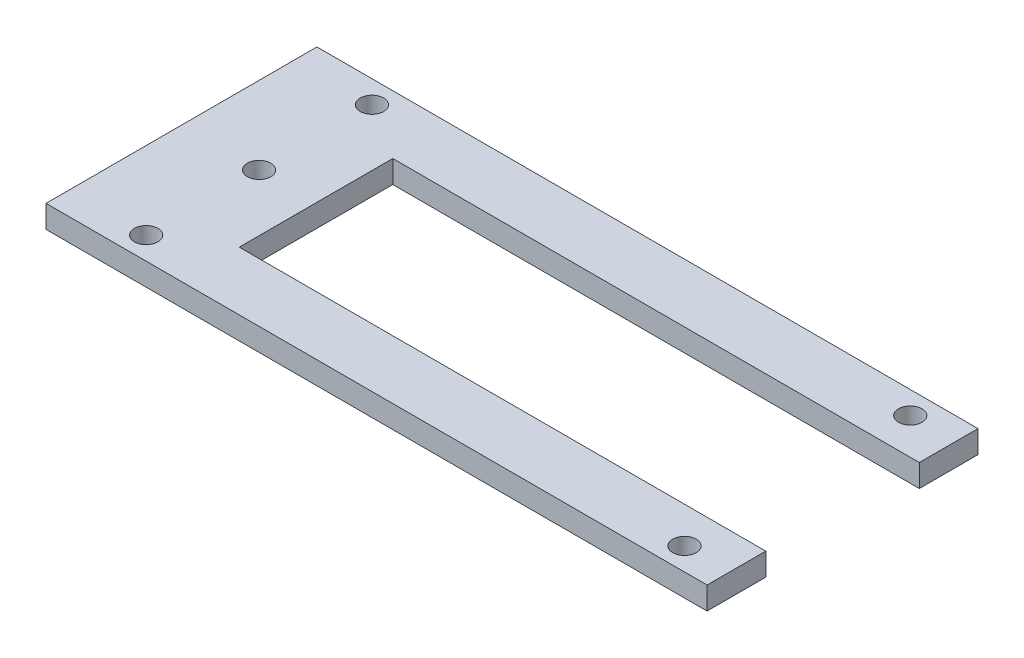
SolidWorks part; units mm, degrees
ref_plane "Front Plane" through (0, 0, 0) normal (0, 0, 1) x (1, 0, 0)
ref_plane "Top Plane" through (0, 0, 0) normal (0, 1, 0) x (1, 0, 0)
ref_plane "Right Plane" through (0, 0, 0) normal (1, 0, 0) x (0, 0, -1)
sketch "Sketch1" plane through (0, 0, 0) normal (0, 1, 0) x (1, 0, 0)
  line L1 (-46.482, -19.05) -> (46.482, -19.05)
  line L2 (-46.482, -19.05) -> (-46.482, 19.05)
  line L3 (-46.482, 19.05) -> (46.482, 19.05)
  line L4 (46.482, -19.05) -> (46.482, 19.05)
  line L5 (-46.482, -19.05) -> (46.482, 19.05) construction
  line L6 (-46.482, 19.05) -> (46.482, -19.05) construction
  circle A0 centre (-35.5677, -15.875) radius 1.651
  circle A1 centre (-35.5677, 15.875) radius 1.651
  circle A2 centre (40.132, 15.875) radius 1.651
  circle A3 centre (40.132, -15.875) radius 1.651
  circle A5 centre (-35.5677, 15.875) radius 1.651 construction
  circle A6 centre (-35.5677, -15.875) radius 1.651 construction
  circle A7 centre (40.132, -15.875) radius 1.651 construction
  circle A8 centre (-35.5677, 0) radius 1.651
  point P0 (0, 0)
  dimension "D1" = 92.964
  dimension "D2" = 38.1
extrude "Boss-Extrude1" add sketch "Sketch1" along normal blind 3.175
sketch "Sketch2" plane through (0, 3.175, 0) normal (0, 1, 0) x (1, 0, 0)
  line L0 (46.482, -19.05) -> (46.482, 19.05) construction
  line L1 (46.482, 10.795) -> (-27.559, 10.795)
  line L2 (46.482, 10.795) -> (46.482, -10.795)
  line L3 (46.482, -10.795) -> (-27.559, -10.795)
  line L4 (-27.559, 10.795) -> (-27.559, -10.795)
  line L5 (-40.132, 10.795) -> (79.2458, 10.795) construction
  line L6 (79.2458, -10.795) -> (-40.132, -10.795) construction
  dimension "D1" = 74.041
extrude "Cut-Extrude1" cut sketch "Sketch2" against normal up to surface (3.175 mm away) up to face at (40.132, 0, 17.526)
